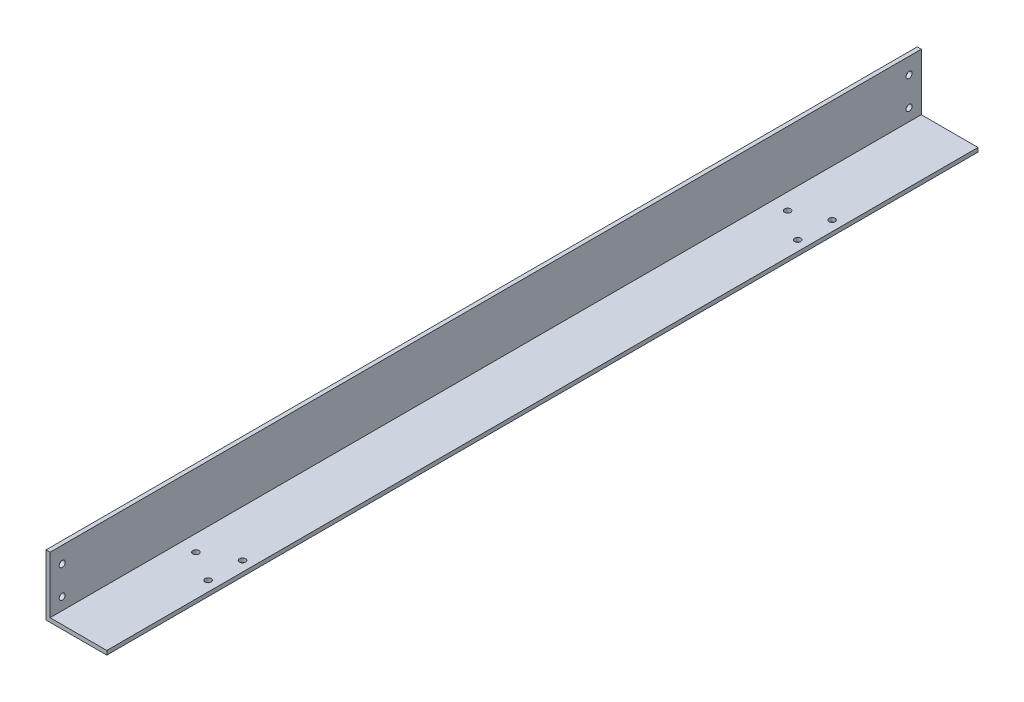
SolidWorks part; units mm, degrees
material "1060 Alloy"
ref_plane "Front Plane" through (0, 0, 0) normal (0, 0, 1) x (1, 0, 0)
ref_plane "Top Plane" through (0, 0, 0) normal (0, 1, 0) x (1, 0, 0)
ref_plane "Right Plane" through (0, 0, 0) normal (1, 0, 0) x (0, 0, -1)
sketch "Sketch1" plane through (0, 0, 0) normal (0, 0, 1) x (1, 0, 0)
  line L0 (0, 5.6023) -> (0, 35.6023)
  line L1 (0, 35.6023) -> (2, 35.6023)
  line L2 (2, 35.6023) -> (2, 7.6023)
  line L3 (2, 7.6023) -> (30, 7.6023)
  line L4 (30, 7.6023) -> (30, 5.6023)
  line L5 (30, 5.6023) -> (0, 5.6023)
extrude "Boss-Extrude1" add sketch "Sketch1" along normal blind 410 and the other way up to vertex (20 mm away)
hole_wizard "Ø3.0 (3) Diameter Hole1" positions "Sketch2" profile "Sketch3" hole size "Ø3.0" standard "ISO"
sketch "Sketch2" plane through (2, -3.8053, 221.32) normal (1, 0, 0) x (0, 0, -1)
  point P0 (-182.68, 17.4076)
  point P1 (-182.68, 31.4076)
sketch "Sketch3" plane through (2, 13.6023, 404) normal (0, 1, 0) x (0, 0, -1)
  line L0 (0, 0) -> (0, 1.999)
  line L1 (0, 1.999) -> (1.5, 1.999)
  line L2 (1.5, 1.999) -> (1.5, 0)
  line L3 (1.5, 0) -> (0, 0)
  line L4 (0, -6.35) -> (0, 107.95) construction
  dimension "Thru Hole Dia." = 3
  dimension "Thru Hole Depth" = 1.999
hole_wizard "Ø3.0 (3) Diameter Hole2" positions "Sketch4" profile "Sketch5" hole size "Ø3.0" standard "ISO"
sketch "Sketch4" plane through (2, -3.8053, 221.32) normal (1, 0, 0) x (0, 0, -1)
  point P0 (235.32, 17.4076)
  point P1 (235.32, 31.4076)
sketch "Sketch5" plane through (2, 13.6023, -14) normal (0, 1, 0) x (0, 0, -1)
  line L0 (0, 0) -> (0, 1.999)
  line L1 (0, 1.999) -> (1.5, 1.999)
  line L2 (1.5, 1.999) -> (1.5, 0)
  line L3 (1.5, 0) -> (0, 0)
  line L4 (0, -6.35) -> (0, 107.95) construction
  dimension "Thru Hole Dia." = 3
  dimension "Thru Hole Depth" = 1.999
hole_wizard "Ø3.0 (3) Diameter Hole3" positions "Sketch6" profile "Sketch7" hole size "Ø3.0" standard "ISO" end condition through all
sketch "Sketch6" plane through (130.862, 5.6023, 221.32) normal (0, -1, 0) x (-1, 0, 0)
  point P0 (105.862, -133.68)
  point P1 (120.862, -124.68)
  point P2 (105.862, -116.68)
sketch "Sketch7" plane through (25, 5.6023, 355) normal (1, 0, 0) x (0, 0, -1)
  line L0 (0, 0) -> (0, 30)
  line L1 (0, 30) -> (1.5, 30)
  line L2 (1.5, 30) -> (1.5, 0)
  line L3 (1.5, 0) -> (0, 0)
  line L4 (0, -6.35) -> (0, 107.95) construction
  dimension "Thru Hole Dia." = 3
  dimension "Thru Hole Depth" = 30
hole_wizard "Ø3.0 (3) Diameter Hole4" positions "Sketch8" profile "Sketch9" hole size "Ø3.0" standard "ISO" end condition through all
sketch "Sketch8" plane through (130.862, 5.6023, 221.32) normal (0, -1, 0) x (-1, 0, 0)
  point P0 (105.862, 174.32)
  point P2 (105.862, 157.32)
  point P4 (120.862, 167.32)
sketch "Sketch9" plane through (25, 5.6023, 47) normal (1, 0, 0) x (0, 0, -1)
  line L0 (0, 0) -> (0, 30)
  line L1 (0, 30) -> (1.5, 30)
  line L2 (1.5, 30) -> (1.5, 0)
  line L3 (1.5, 0) -> (0, 0)
  line L4 (0, -6.35) -> (0, 107.95) construction
  dimension "Thru Hole Dia." = 3
  dimension "Thru Hole Depth" = 30
